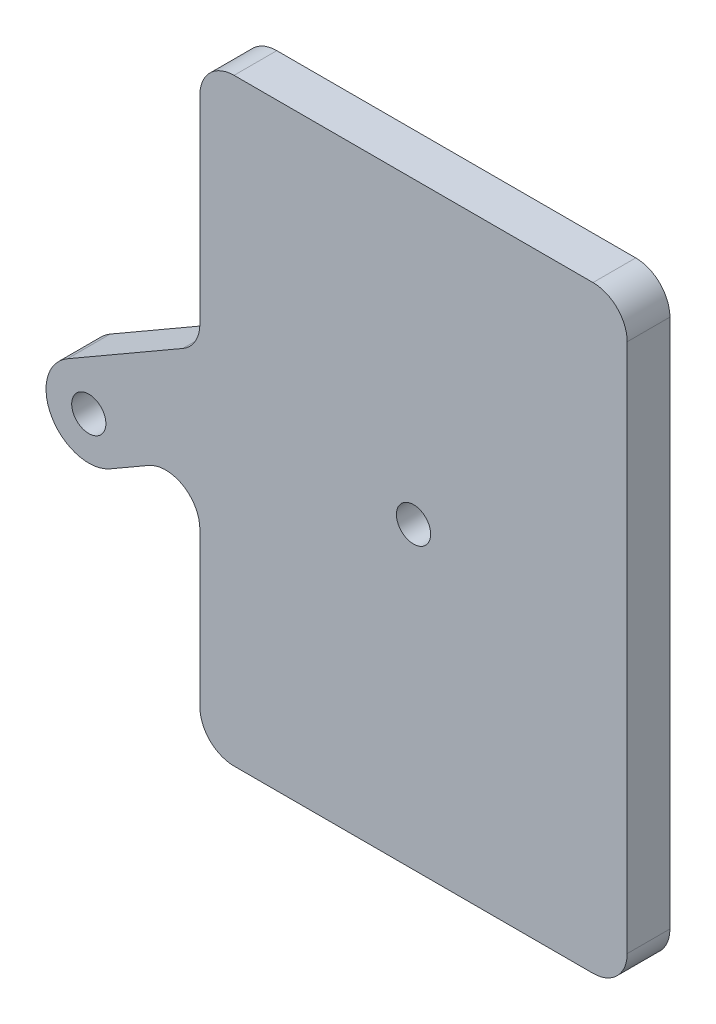
SolidWorks part; units mm, degrees
ref_plane "前基準面" through (0, 0, 0) normal (0, 0, 1) x (1, 0, 0)
ref_plane "上基準面" through (0, 0, 0) normal (0, 1, 0) x (1, 0, 0)
ref_plane "右基準面" through (0, 0, 0) normal (1, 0, 0) x (0, 0, -1)
sketch "草圖1" plane through (0, 0, 0) normal (0, 0, 1) x (1, 0, 0)
  line L0 (0, 0) -> (0, -7.8) construction
  line L1 (-21, -35) -> (21, -35)
  line L2 (-25, -31) -> (-25, -12.9962)
  line L3 (-21, 35) -> (21, 35)
  line L4 (25, -31) -> (25, 31)
  line L5 (-25, -35) -> (25, 35) construction
  line L6 (-25, 35) -> (25, -35) construction
  line L7 (0, -7.8) -> (-38, -7.8) construction
  line L8 (0, 0) -> (-25, 0) construction
  line L9 (-25, 0) -> (-38, -7.8) construction
  line L12 (-31, -9.5321) -> (-35.5, -12.1301)
  line L13 (-27, 4.3244) -> (-40.5, -3.4699)
  line L14 (-25, 7.7885) -> (-25, 31)
  circle A0 centre (0, 0) radius 2
  arc A4 (-40.5, -3.4699) -> (-35.5, -12.1301) centre (-38, -7.8) ccw
  circle A5 centre (-38, -7.8) radius 2
  arc A6 (21, 35) -> (25, 31) centre (21, 31) cw
  arc A7 (21, -35) -> (25, -31) centre (21, -31) ccw
  arc A8 (-25, -12.9962) -> (-31, -9.5321) centre (-29, -12.9962) ccw
  arc A9 (-21, -35) -> (-25, -31) centre (-21, -31) cw
  arc A10 (-25, 31) -> (-21, 35) centre (-21, 31) cw
  arc A11 (-25, 7.7885) -> (-27, 4.3244) centre (-29, 7.7885) cw
  point P0 (0, 0)
  point P8 (-31.5, -3.9)
  point P14 (-25, 5.411)
  dimension "D3" = 4
  dimension "D6" = 5
  dimension "D7" = 4
  dimension "D11" = 4
  dimension "D1" = 50
  dimension "D2" = 70
  dimension "D4" = 7.8
  dimension "D5" = 38
  dimension "D8" = 15.1605
  dimension "D9" = 10
  dimension "D10" = 120
extrude "填料-伸長1" add sketch "草圖1" along normal mid plane 5
